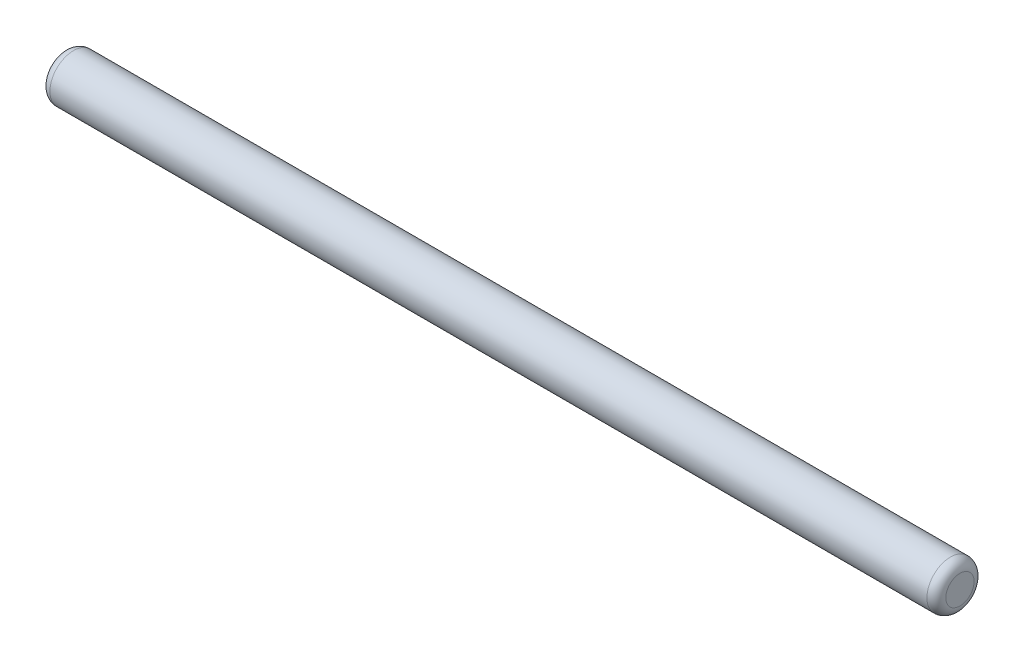
SolidWorks part; units mm, degrees
material "1060 Alloy"
ref_plane "Front Plane" through (0, 0, 0) normal (0, 0, 1) x (1, 0, 0)
ref_plane "Top Plane" through (0, 0, 0) normal (0, 1, 0) x (1, 0, 0)
ref_plane "Right Plane" through (0, 0, 0) normal (1, 0, 0) x (0, 0, -1)
sketch "Sketch1" plane through (0, 0, 0) normal (1, 0, 0) x (0, 0, -1)
  circle A0 centre (0, 0) radius 3.175
  dimension "D1" = 6.35
extrude "Boss-Extrude1" add sketch "Sketch1" along normal blind 120.65
fillet "Fillet1" radius 1.27 2 edges at (0, 0, -3.175) (120.65, 0, -3.175)
